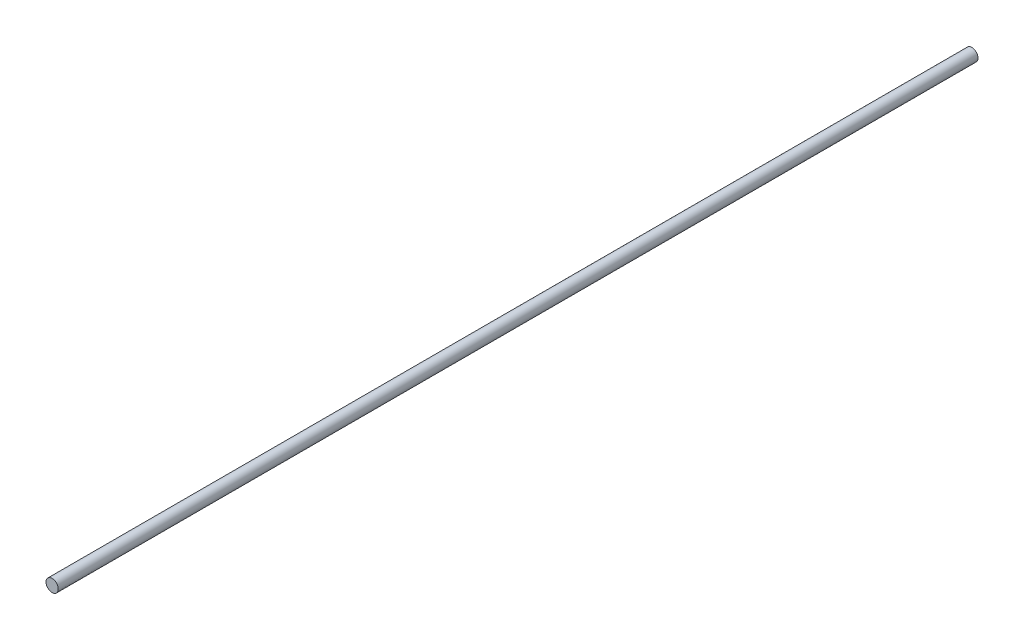
SolidWorks part; units mm, degrees
ref_plane "Płaszczyzna przednia" through (0, 0, 0) normal (0, 0, 1) x (1, 0, 0)
ref_plane "Płaszczyzna górna" through (0, 0, 0) normal (0, 1, 0) x (1, 0, 0)
ref_plane "Płaszczyzna prawa" through (0, 0, 0) normal (1, 0, 0) x (0, 0, -1)
sketch "Szkic1" plane through (0, 0, 0) normal (0, 0, 1) x (1, 0, 0)
  circle A0 centre (0, 0) radius 1.5
  dimension "D1" = 3
extrude "Dodanie-wyciągnięcie1" add sketch "Szkic1" along normal blind 225
